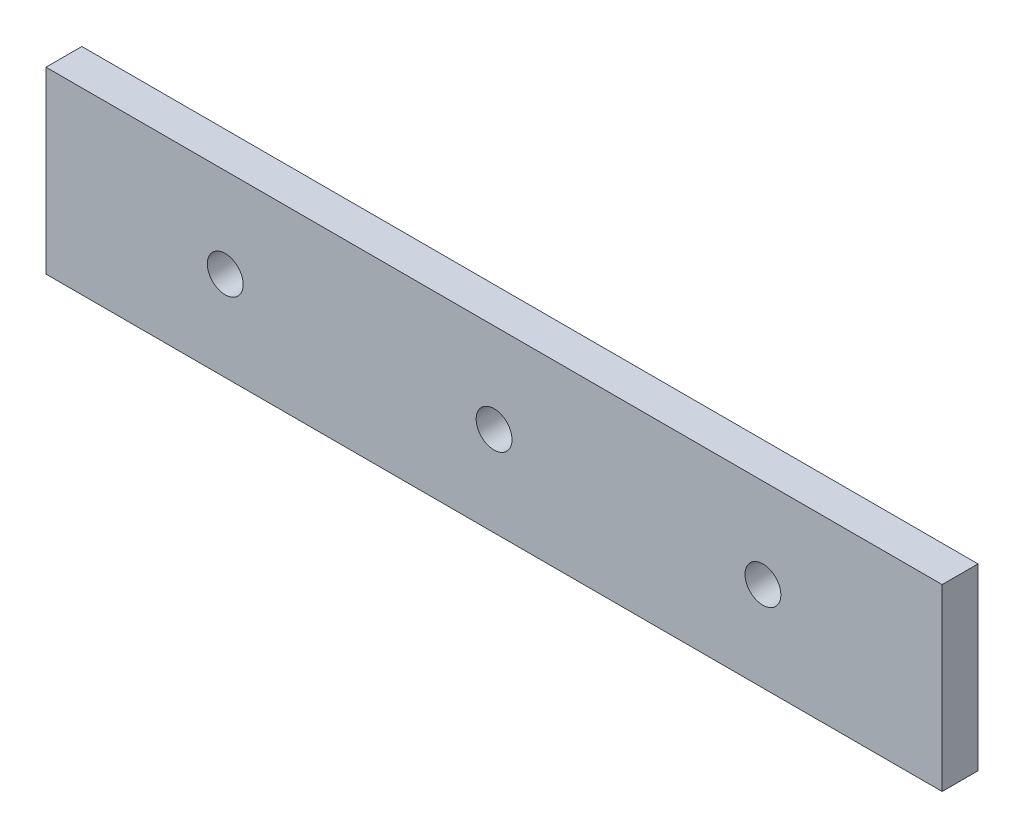
SolidWorks part; units mm, degrees
ref_plane "Front Plane" through (0, 0, 0) normal (0, 0, 1) x (1, 0, 0)
ref_plane "Top Plane" through (0, 0, 0) normal (0, 1, 0) x (1, 0, 0)
ref_plane "Right Plane" through (0, 0, 0) normal (1, 0, 0) x (0, 0, -1)
sketch "Sketch1" plane through (0, 0, 0) normal (0, 0, 1) x (1, 0, 0)
  line L1 (0, 0) -> (75, 0)
  line L2 (0, 0) -> (0, 15)
  line L3 (0, 15) -> (75, 15)
  line L4 (75, 0) -> (75, 15)
  circle A0 centre (15, 7.5) radius 1.5
  circle A1 centre (37.5, 7.5) radius 1.5
  circle A2 centre (60, 7.5) radius 1.5
  dimension "D3" = 3
  dimension "D4" = 3
  dimension "D5" = 3
  dimension "D1" = 75
  dimension "D2" = 15
  dimension "D6" = 15
  dimension "D7" = 37.5
  dimension "D8" = 7.5
  dimension "D9" = 7.5
  dimension "D10" = 7.5
  dimension "D11" = 15
extrude "Boss-Extrude1" add sketch "Sketch1" along normal blind 3
